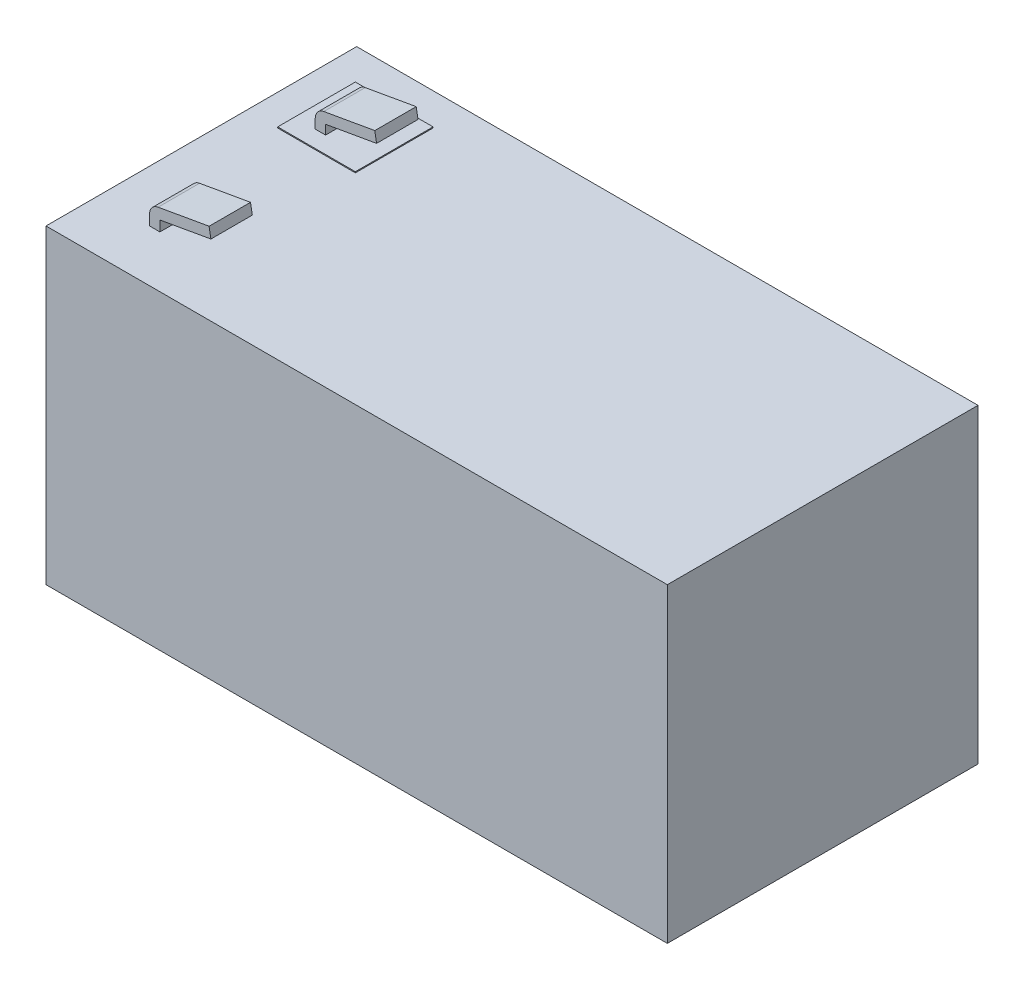
SolidWorks part; units mm, degrees
material "CA"
ref_plane "Front" through (0, 0, 0) normal (0, 0, 1) x (1, 0, 0)
ref_plane "Top" through (0, 0, 0) normal (0, 1, 0) x (1, 0, 0)
ref_plane "Right" through (0, 0, 0) normal (1, 0, 0) x (0, 0, -1)
sketch "Sketch1" plane through (0, 0, 0) normal (0, 1, 0) x (1, 0, 0)
  line L1 (-76.2, 38.1) -> (76.2, 38.1)
  line L2 (-76.2, 38.1) -> (-76.2, -38.1)
  line L3 (-76.2, -38.1) -> (76.2, -38.1)
  line L4 (76.2, 38.1) -> (76.2, -38.1)
  point P4 (0, 38.1)
  point P6 (-76.2, 0)
  dimension "D1" = 152.4
  dimension "D2" = 76.2
extrude "Boss-Extrude1" add sketch "Sketch1" along normal blind 76.2
sketch "Sketch2" plane through (0, 76.2, 0) normal (0, 1, 0) x (1, 0, 0)
  line L0 (0, 0) -> (-63.5, 0) construction
  line L1 (-63.5, 25.4) -> (-60.96, 25.4)
  line L2 (-63.5, 25.4) -> (-63.5, 15.24)
  line L3 (-63.5, 15.24) -> (-60.96, 15.24)
  line L4 (-60.96, 25.4) -> (-60.96, 15.24)
  line L5 (-63.5, -15.24) -> (-60.96, -15.24)
  line L6 (-63.5, -15.24) -> (-63.5, -25.4)
  line L7 (-63.5, -25.4) -> (-60.96, -25.4)
  line L8 (-60.96, -15.24) -> (-60.96, -25.4)
  line L9 (-63.5, 15.24) -> (-63.5, -15.24) construction
  line L10 (-76.2, -38.1) -> (76.2, -38.1) construction
  point P11 (-63.5, 0)
  dimension "D1" = 2.54
  dimension "D2" = 10.16
  dimension "D3" = 12.7
  dimension "D4" = 63.5
sketch "Sketch4" plane through (0, 0, 0) normal (0, 0, 1) x (1, 0, 0)
  line L0 (-62.23, 76.2) -> (-62.23, 78.74)
  line L1 (-63.5, 76.2) -> (-60.96, 76.2) construction
  line L2 (-61.1805, 79.9907) -> (-48.6735, 82.196)
  arc A0 (-61.1805, 79.9907) -> (-62.23, 78.74) centre (-60.96, 78.74) ccw
  dimension "D1" = 1.27
  dimension "D2" = 2.54
  dimension "D3" = 12.7
  dimension "D4" = 100
sweep "Sweep1" add profiles "Sketch2" path "Sketch4"
sketch "Sketch5" plane through (0, 76.2, 0) normal (0, 1, 0) x (1, 0, 0)
  line L0 (76.2, 38.1) -> (-76.2, 38.1) construction
  line L1 (-68.58, 30.1625) -> (-49.53, 30.1625)
  line L2 (-68.58, 30.1625) -> (-68.58, 11.1125)
  line L3 (-68.58, 11.1125) -> (-49.53, 11.1125)
  line L4 (-49.53, 30.1625) -> (-49.53, 11.1125)
  line L5 (-76.2, 38.1) -> (-76.2, -38.1) construction
  dimension "D1" = 7.9375
  dimension "D2" = 7.62
  dimension "D3" = 19.05
  dimension "D4" = 19.05
extrude "Boss-Extrude2" add sketch "Sketch5" along normal blind 0.254
